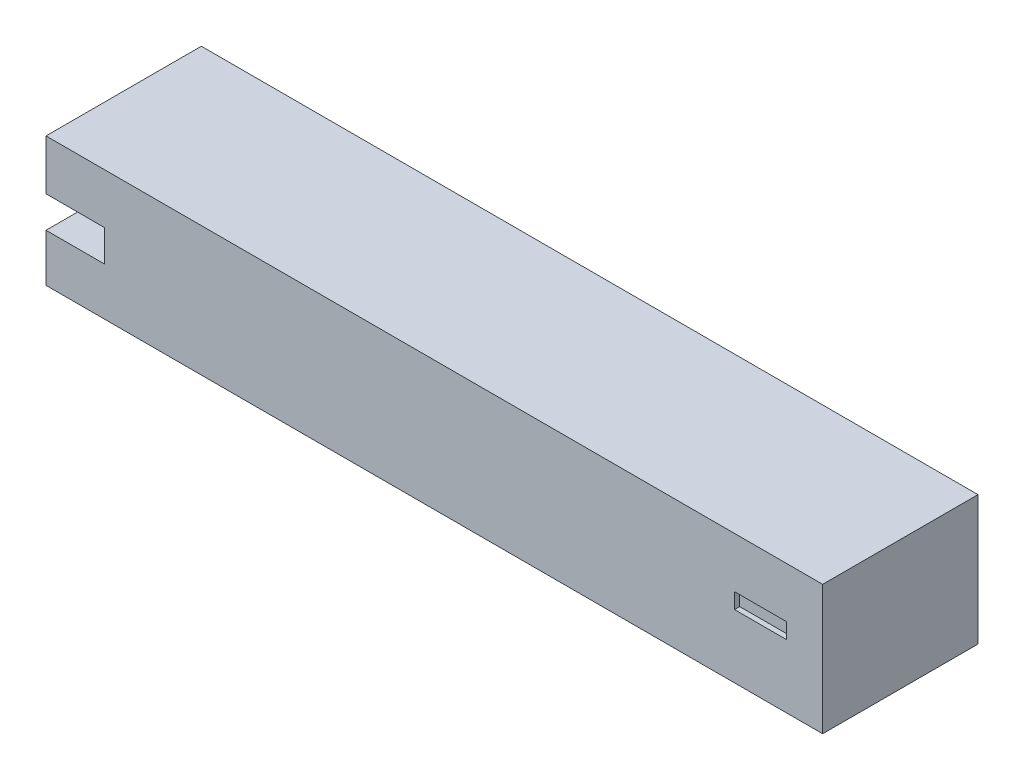
SolidWorks part; units mm, degrees
ref_plane "Front Plane" through (0, 0, 0) normal (0, 0, 1) x (1, 0, 0)
ref_plane "Top Plane" through (0, 0, 0) normal (0, 1, 0) x (1, 0, 0)
ref_plane "Right Plane" through (0, 0, 0) normal (1, 0, 0) x (0, 0, -1)
sketch "Sketch1" plane through (0, 0, 0) normal (0, 0, 1) x (1, 0, 0)
  line L1 (0, 0) -> (300, 0)
  line L2 (0, 0) -> (0, -50)
  line L3 (0, -50) -> (300, -50)
  line L4 (300, 0) -> (300, -50)
  dimension "D1" = 300
  dimension "D2" = 50
extrude "Boss-Extrude1" add sketch "Sketch1" along normal blind 60
sketch "Sketch4" plane through (0, 0, 60) normal (0, 0, 1) x (1, 0, 0)
  line L0 (150, 0) -> (150, -50) construction
  line L1 (0, 0) -> (300, 0) construction
  line L2 (0, -50) -> (300, -50) construction
  line L3 (0, -25) -> (300, -25) construction
  line L4 (0, 0) -> (0, -50) construction
  line L5 (300, 0) -> (300, -50) construction
  line L11 (265.9591, -19.4797) -> (285.9591, -19.4797)
  line L12 (265.9591, -19.4797) -> (265.9591, -25.4797)
  line L13 (265.9591, -25.4797) -> (285.9591, -25.4797)
  line L14 (285.9591, -19.4797) -> (285.9591, -25.4797)
  dimension "D1" = 20
  dimension "D2" = 6
sketch "Sketch5" plane through (0, 0, 60) normal (0, 0, 1) x (1, 0, 0)
  line L5 (0, 0) -> (0, -50) construction
  line L6 (0, -19.3737) -> (22.63, -19.3737)
  line L7 (0, -19.3737) -> (0, -31.5637)
  line L8 (0, -31.5637) -> (22.63, -31.5637)
  line L9 (22.63, -19.3737) -> (22.63, -31.5637)
  line L10 (0, 0) -> (300, 0) construction
  dimension "D1" = 22.63
  dimension "D2" = 12.19
  dimension "D3" = 19.3737
extrude "Cut-Extrude2" cut sketch "Sketch5" against normal blind 12.84
extrude "Cut-Extrude3" cut sketch "Sketch4" against normal blind 2
